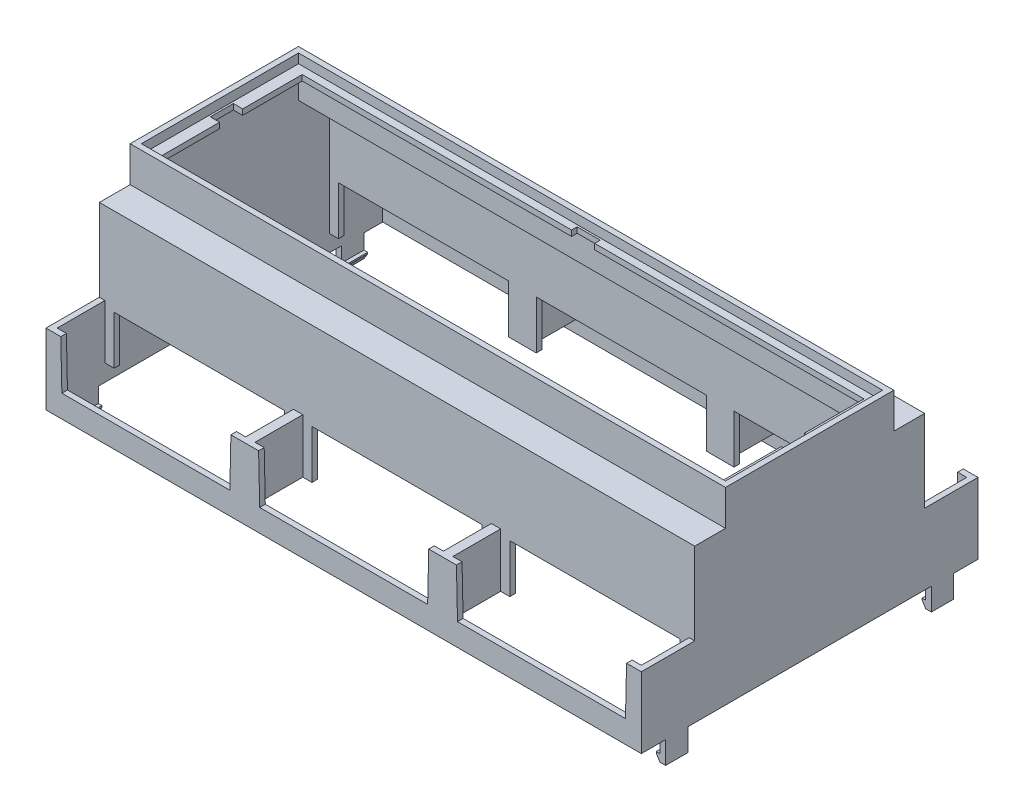
SolidWorks part; units mm, degrees
ref_plane "Спереди" through (0, 0, 0) normal (0, 0, 1) x (1, 0, 0)
ref_plane "Сверху" through (0, 0, 0) normal (0, 1, 0) x (1, 0, 0)
ref_plane "Справа" through (0, 0, 0) normal (1, 0, 0) x (0, 0, -1)
sketch "Эскиз1" plane through (0, 0, 0) normal (0, 1, 0) x (1, 0, 0)
  line L1 (79.75, -45.1) -> (-79.75, -45.1)
  line L2 (79.75, -45.1) -> (79.75, 45.1)
  line L3 (79.75, 45.1) -> (-79.75, 45.1)
  line L4 (-79.75, -45.1) -> (-79.75, 45.1)
  line L5 (79.75, -45.1) -> (-79.75, 45.1) construction
  line L6 (79.75, 45.1) -> (-79.75, -45.1) construction
  point P0 (0, 0)
  dimension "D1" = 159.5
  dimension "D2" = 90.2
extrude "Бобышка-Вытянуть1" add sketch "Эскиз1" along normal blind 50.5
sketch "Эскиз2" plane through (79.75, 0, 0) normal (1, 0, 0) x (0, 0, -1)
  line L0 (-46.1, 19) -> (-30.8, 19)
  line L1 (-30.8, 19) -> (-30.8, 41)
  line L2 (-30.8, 41) -> (-22.55, 41)
  line L3 (-22.55, 41) -> (-22.55, 51.5)
  line L4 (-22.55, 51.5) -> (22.55, 51.5)
  line L5 (22.55, 51.5) -> (22.55, 41)
  line L6 (22.55, 41) -> (30.8, 41)
  line L7 (30.8, 41) -> (30.8, 19)
  line L8 (30.8, 19) -> (46.1, 19)
  line L9 (46.1, 19) -> (46.1, 52.5)
  line L10 (46.1, 52.5) -> (-46.1, 52.5)
  line L11 (-46.1, 52.5) -> (-46.1, 19)
  line L12 (-45.1, 0) -> (45.1, 0) construction
  line L13 (-45.1, 50.5) -> (-45.1, 0) construction
  line L14 (-45.1, 50.5) -> (45.1, 50.5) construction
  line L15 (45.1, 50.5) -> (45.1, 0) construction
  dimension "D1" = 19
  dimension "D2" = 1
  dimension "D3" = 1
  dimension "D4" = 1
  dimension "D5" = 19
  dimension "D6" = 61.6
  dimension "D7" = 30.8
  dimension "D8" = 41
  dimension "D9" = 41
  dimension "D10" = 45.1
  dimension "D11" = 22.55
  dimension "D12" = 2
extrude "Вырез-Вытянуть1" cut sketch "Эскиз2" against normal through all
shell "Оболочка1" thickness 1.5
sketch "Эскиз3" plane through (79.75, 0, 0) normal (1, 0, 0) x (0, 0, -1)
  line L1 (-45.1, 19) -> (-45.1, 0) construction
  line L2 (-38.6, 0) -> (-32.6, 0)
  line L3 (-38.6, 0) -> (-38.6, -6)
  line L4 (-38.6, -6) -> (-32.6, -6)
  line L6 (-32.6, 0) -> (-32.6, -6)
  line L7 (-38.6, 0) -> (-32.6, -6) construction
  line L8 (-38.6, -6) -> (-32.6, 0) construction
  line L9 (-45.1, 0) -> (45.1, 0) construction
  point P0 (-35.6, -3)
  dimension "D1" = 6
  dimension "D2" = 6
  dimension "D3" = 9.5
  dimension "D4" = 6.5
  dimension "D5" = 0
extrude "Бобышка-Вытянуть3" add sketch "Эскиз3" against normal blind 1.5
sketch "Эскиз4" plane through (0, 0, 38.6) normal (0, 0, 1) x (1, 0, 0)
  line L0 (78.25, -6) -> (77.25, -4.4)
  line L1 (77.25, -4.4) -> (77.25, -4)
  line L2 (77.25, -4) -> (78.75, -4)
  line L3 (78.75, -4) -> (78.75, -6)
  line L4 (78.25, -6) -> (79.75, -6) construction
  line L5 (78.75, -6) -> (78.25, -6)
  line L6 (78.25, 0) -> (78.25, -6) construction
  dimension "D1" = 2
  dimension "D2" = 1.6
  dimension "D3" = 0.5
  dimension "D4" = 1
extrude "Бобышка-Вытянуть4" add sketch "Эскиз4" against normal blind 6
mirror "Зеркальное отражение1" about plane through (0, 0, 0) normal (0, 0, 1) of "Бобышка-Вытянуть4", "Бобышка-Вытянуть3"
mirror "Зеркальное отражение2" about plane through (0, 0, 0) normal (1, 0, 0) of "Зеркальное отражение1", "Бобышка-Вытянуть4", "Бобышка-Вытянуть3"
sketch "Эскиз6" plane through (0, 19, 0) normal (0, 1, 0) x (1, 0, 0)
  line L0 (79.75, -45.1) -> (-79.75, -45.1) construction
  line L1 (25.25, -43.6) -> (-25.25, -43.6)
  line L2 (25.25, -43.6) -> (25.25, -30.8)
  line L3 (25.25, -30.8) -> (-25.25, -30.8)
  line L4 (-25.25, -43.6) -> (-25.25, -30.8)
  line L5 (25.25, -43.6) -> (-25.25, -30.8) construction
  line L6 (25.25, -30.8) -> (-25.25, -43.6) construction
  line L7 (-79.75, -30.8) -> (79.75, -30.8) construction
  line L8 (-79.75, 22.55) -> (-79.75, -22.55) construction
  line L9 (-78.25, -30.8) -> (-27.75, -30.8)
  line L10 (-78.25, -30.8) -> (-78.25, -43.6)
  line L11 (-78.25, -43.6) -> (-27.75, -43.6)
  line L12 (-27.75, -30.8) -> (-27.75, -43.6)
  line L13 (-78.25, -30.8) -> (-27.75, -43.6) construction
  line L14 (-78.25, -43.6) -> (-27.75, -30.8) construction
  line L15 (27.75, -30.8) -> (78.25, -30.8)
  line L16 (27.75, -30.8) -> (27.75, -43.6)
  line L17 (27.75, -43.6) -> (78.25, -43.6)
  line L18 (78.25, -30.8) -> (78.25, -43.6)
  line L19 (27.75, -30.8) -> (78.25, -43.6) construction
  line L20 (27.75, -43.6) -> (78.25, -30.8) construction
  line L21 (79.75, -45.1) -> (79.75, -30.8) construction
  point P0 (0, -37.2)
  point P10 (-53, -37.2)
  point P15 (53, -37.2)
  dimension "D1" = 50.5
  dimension "D2" = 0
  dimension "D3" = 1.5
  dimension "D4" = 0
  dimension "D5" = 50.5
  dimension "D6" = 1.5
  dimension "D7" = 0
  dimension "D8" = 1.5
  dimension "D9" = 50.5
  dimension "D10" = 0
  dimension "D11" = 1.5
  dimension "D12" = 1.5
  dimension "D13" = 2.5
  dimension "D14" = 2.5
  dimension "D15" = 53
  dimension "D16" = 53
extrude "Вырез-Вытянуть2" cut sketch "Эскиз6" against normal blind 20
sketch "Эскиз7" plane through (0, 0, 45.1) normal (0, 0, 1) x (1, 0, 0)
  line L0 (-22.8, 19.5) -> (-22.5, 6)
  line L1 (-22.5, 6) -> (22.5, 6)
  line L2 (22.5, 6) -> (22.8, 19.5)
  line L3 (22.8, 19.5) -> (-22.8, 19.5)
  line L4 (79.75, 19) -> (-79.75, 19) construction
  line L5 (-79.75, 0) -> (79.75, 0) construction
  dimension "D1" = 22.8
  dimension "D2" = 22.8
  dimension "D3" = 0.3
  dimension "D4" = 0.3
  dimension "D5" = 0.5
  dimension "D6" = 6
  dimension "D7" = 13.5
extrude "Вырез-Вытянуть3" cut sketch "Эскиз7" against normal blind 10
pattern_linear "Линейный массив1" count 2 spacing 53 along (1, 0, 0) count 2 spacing 53 along (-1, 0, 0) of "Вырез-Вытянуть3"
sketch "Эскиз8" plane through (0, 17.5, 0) normal (0, -1, 0) x (1, 0, 0)
  line L0 (-30.2, 30.8) -> (-30.2, 29.3)
  line L1 (-78.25, 30.8) -> (-27.75, 30.8) construction
  line L2 (-78.25, 29.3) -> (78.25, 29.3) construction
  line L3 (-30.2, 29.3) -> (-22.8, 29.3)
  line L4 (-22.8, 29.3) -> (-22.8, 30.8)
  line L5 (-25.25, 30.8) -> (25.25, 30.8) construction
  line L6 (-22.8, 30.8) -> (-25.25, 30.8)
  line L7 (-25.25, 43.6) -> (-25.25, 30.8) construction
  line L8 (-25.25, 30.8) -> (-25.25, 43.6)
  line L9 (-25.25, 43.6) -> (-27.75, 43.6)
  line L10 (-27.75, 43.6) -> (-27.75, 30.8)
  line L11 (-27.75, 30.8) -> (-30.2, 30.8)
  line L12 (22.8, 30.8) -> (22.8, 29.3)
  line L13 (22.8, 29.3) -> (30.2, 29.3)
  line L14 (30.2, 29.3) -> (30.2, 30.8)
  line L15 (27.75, 30.8) -> (78.25, 30.8) construction
  line L16 (30.2, 30.8) -> (27.75, 30.8)
  line L17 (27.75, 30.8) -> (27.75, 43.6)
  line L18 (27.75, 43.6) -> (25.25, 43.6)
  line L19 (25.25, 43.6) -> (25.25, 30.8)
  line L20 (25.25, 30.8) -> (22.8, 30.8)
  line L21 (-78.25, 30.8) -> (-75.8, 30.8)
  line L22 (-75.8, 30.8) -> (-75.8, 29.3)
  line L23 (-78.25, 29.3) -> (78.25, 29.3) construction
  line L24 (-75.8, 29.3) -> (-78.25, 29.3)
  line L25 (-78.25, 29.3) -> (-78.25, 30.8)
  line L26 (78.25, 30.8) -> (78.25, 29.3)
  line L27 (78.25, 29.3) -> (75.8, 29.3)
  line L28 (75.8, 29.3) -> (75.8, 30.8)
  line L29 (75.8, 30.8) -> (78.25, 30.8)
  dimension "D1" = 7.4
  dimension "D2" = 2.5
  dimension "D3" = 2.45
  dimension "D4" = 2.45
  dimension "D5" = 2.45
  dimension "D6" = 7.4
  dimension "D7" = 2.5
  dimension "D8" = 2.45
  dimension "D9" = 2.45
extrude "Бобышка-Вытянуть5" add sketch "Эскиз8" along normal blind 16
sketch "Эскиз9" plane through (0, 0, 0) normal (0, -1, 0) x (1, 0, 0)
  line L1 (-78.25, 43.6) -> (78.25, 43.6)
  line L2 (-78.25, 43.6) -> (-78.25, 21.05)
  line L3 (-78.25, 21.05) -> (78.25, 21.05)
  line L4 (78.25, 43.6) -> (78.25, 21.05)
extrude "Вырез-Вытянуть4" cut sketch "Эскиз9" against normal blind 4.5
mirror "Зеркальное отражение3" about plane through (0, 0, 0) normal (0, 0, 1) of "Вырез-Вытянуть4", "Бобышка-Вытянуть5", "Линейный массив1", "Вырез-Вытянуть3", "Вырез-Вытянуть2"
sketch "Эскиз10" plane through (0, 50.5, 0) normal (0, 1, 0) x (1, 0, 0)
  line L2 (79.75, -22.55) -> (-79.75, -22.55)
  line L3 (79.75, -22.55) -> (79.75, 22.55)
  line L4 (79.75, 22.55) -> (-79.75, 22.55)
  line L5 (-79.75, -22.55) -> (-79.75, 22.55)
  line L6 (79.75, -22.55) -> (-79.75, 22.55) construction
  line L8 (79.75, 22.55) -> (-79.75, -22.55) construction
  point P0 (0, 0)
extrude "Бобышка-Вытянуть6" add sketch "Эскиз10" against normal blind 4
sketch "Эскиз11" plane through (0, 50.5, 0) normal (0, 1, 0) x (1, 0, 0)
  line L0 (-79.75, 22.55) -> (-79.75, -22.55) construction
  line L1 (78.25, -21.05) -> (-78.25, -21.05)
  line L2 (78.25, -21.05) -> (78.25, 21.05)
  line L3 (78.25, 21.05) -> (-78.25, 21.05)
  line L4 (-78.25, -21.05) -> (-78.25, 21.05)
  line L5 (78.25, -21.05) -> (-78.25, 21.05) construction
  line L6 (78.25, 21.05) -> (-78.25, -21.05) construction
  line L7 (-79.75, 22.55) -> (79.75, 22.55) construction
  point P0 (0, 0)
  dimension "D1" = 1.5
  dimension "D2" = 1.5
  dimension "D3" = 156.5
  dimension "D4" = 42.1
extrude "Вырез-Вытянуть6" cut sketch "Эскиз11" against normal blind 2.5
sketch "Эскиз12" plane through (0, 48, 0) normal (0, 1, 0) x (1, 0, 0)
  line L0 (-78.25, 21.05) -> (-78.25, -21.05) construction
  line L1 (75.25, -19.05) -> (-75.25, -19.05)
  line L2 (75.25, -19.05) -> (75.25, 19.05)
  line L3 (75.25, 19.05) -> (-75.25, 19.05)
  line L4 (-75.25, -19.05) -> (-75.25, 19.05)
  line L5 (75.25, -19.05) -> (-75.25, 19.05) construction
  line L6 (75.25, 19.05) -> (-75.25, -19.05) construction
  line L7 (78.25, 21.05) -> (-78.25, 21.05) construction
  point P0 (0, 0)
  dimension "D1" = 3
  dimension "D2" = 2
extrude "Вырез-Вытянуть7" cut sketch "Эскиз12" against normal blind 4
sketch "Эскиз13" plane through (0, 48, 0) normal (0, 1, 0) x (1, 0, 0)
  line L0 (-78.25, 21.05) -> (-78.25, -21.05) construction
  line L1 (-77.75, 3.1) -> (-73.75, 3.1)
  line L2 (-77.75, 3.1) -> (-77.75, -3.1)
  line L3 (-77.75, -3.1) -> (-73.75, -3.1)
  line L4 (-73.75, 3.1) -> (-73.75, -3.1)
  line L5 (-77.75, 3.1) -> (-73.75, -3.1) construction
  line L6 (-77.75, -3.1) -> (-73.75, 3.1) construction
  line L7 (78.25, 21.05) -> (-78.25, 21.05) construction
  line L8 (-3.1, 20.55) -> (3.1, 20.55)
  line L9 (-3.1, 20.55) -> (-3.1, 16.55)
  line L10 (-3.1, 16.55) -> (3.1, 16.55)
  line L11 (3.1, 20.55) -> (3.1, 16.55)
  line L12 (-3.1, 20.55) -> (3.1, 16.55) construction
  line L13 (-3.1, 16.55) -> (3.1, 20.55) construction
  line L14 (-3.1, -16.55) -> (3.1, -16.55)
  line L15 (-3.1, -16.55) -> (-3.1, -20.55)
  line L16 (-3.1, -20.55) -> (3.1, -20.55)
  line L17 (3.1, -16.55) -> (3.1, -20.55)
  line L18 (-3.1, -16.55) -> (3.1, -20.55) construction
  line L19 (-3.1, -20.55) -> (3.1, -16.55) construction
  line L20 (73.75, 3.1) -> (77.75, 3.1)
  line L21 (73.75, 3.1) -> (73.75, -3.1)
  line L22 (73.75, -3.1) -> (77.75, -3.1)
  line L23 (77.75, 3.1) -> (77.75, -3.1)
  line L24 (73.75, 3.1) -> (77.75, -3.1) construction
  line L25 (73.75, -3.1) -> (77.75, 3.1) construction
  line L26 (-78.25, -21.05) -> (78.25, -21.05) construction
  line L27 (78.25, -21.05) -> (78.25, 21.05) construction
  point P0 (-75.75, 0)
  point P8 (0, 18.55)
  point P13 (0, -18.55)
  point P18 (75.75, 0)
  dimension "D1" = 6.2
  dimension "D2" = 0.5
  dimension "D3" = 0
  dimension "D4" = 4
  dimension "D5" = 6.2
  dimension "D6" = 4
  dimension "D7" = 6.2
  dimension "D8" = 4
  dimension "D9" = 6.2
  dimension "D10" = 4
  dimension "D11" = 0
  dimension "D12" = 0.5
  dimension "D13" = 0.5
  dimension "D14" = 0
  dimension "D15" = 0.5
  dimension "D16" = 0
extrude "Вырез-Вытянуть8" cut sketch "Эскиз13" against normal blind 4
